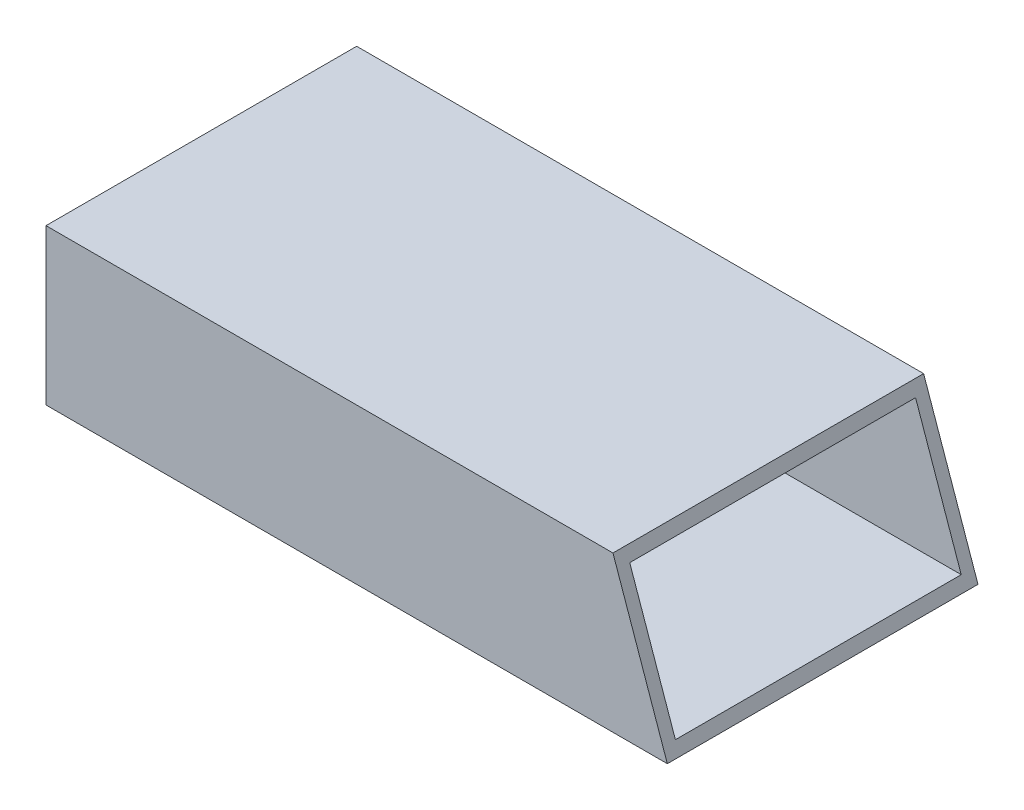
SolidWorks part; units mm, degrees
ref_plane "Płaszczyzna przednia" through (0, 0, 0) normal (0, 0, 1) x (1, 0, 0)
ref_plane "Płaszczyzna górna" through (0, 0, 0) normal (0, 1, 0) x (1, 0, 0)
ref_plane "Płaszczyzna prawa" through (0, 0, 0) normal (1, 0, 0) x (0, 0, -1)
sketch "Szkic1" plane through (0, 0, 0) normal (0, 0, 1) x (1, 0, 0)
  line L0 (0, 0) -> (200, 0)
  line L1 (200, 0) -> (182.5, 50)
  line L3 (0, 50) -> (0, 0)
  line L4 (0, 50) -> (182.5, 50)
  dimension "D1" = 200
  dimension "D3" = 50
  dimension "D6" = 182.5
extrude "Dodanie-wyciągnięcie1" add sketch "Szkic1" along normal blind 100
sketch "Szkic2" plane through (0, 0, 0) normal (-1, 0, 0) x (0, 0, 1)
  line L0 (4, 4) -> (96, 4)
  line L1 (96, 4) -> (96, 46)
  line L2 (96, 46) -> (4, 46)
  line L3 (4, 46) -> (4, 4)
  line L4 (100, 0) -> (0, 0) construction
  line L5 (100, 50) -> (100, 0) construction
  line L6 (0, 50) -> (0, 0) construction
  line L7 (100, 50) -> (0, 50) construction
  dimension "D1" = 4
  dimension "D2" = 4
  dimension "D3" = 4
  dimension "D4" = 4
extrude "Wytnij-wyciągnięcie1" cut sketch "Szkic2" against normal blind 200
